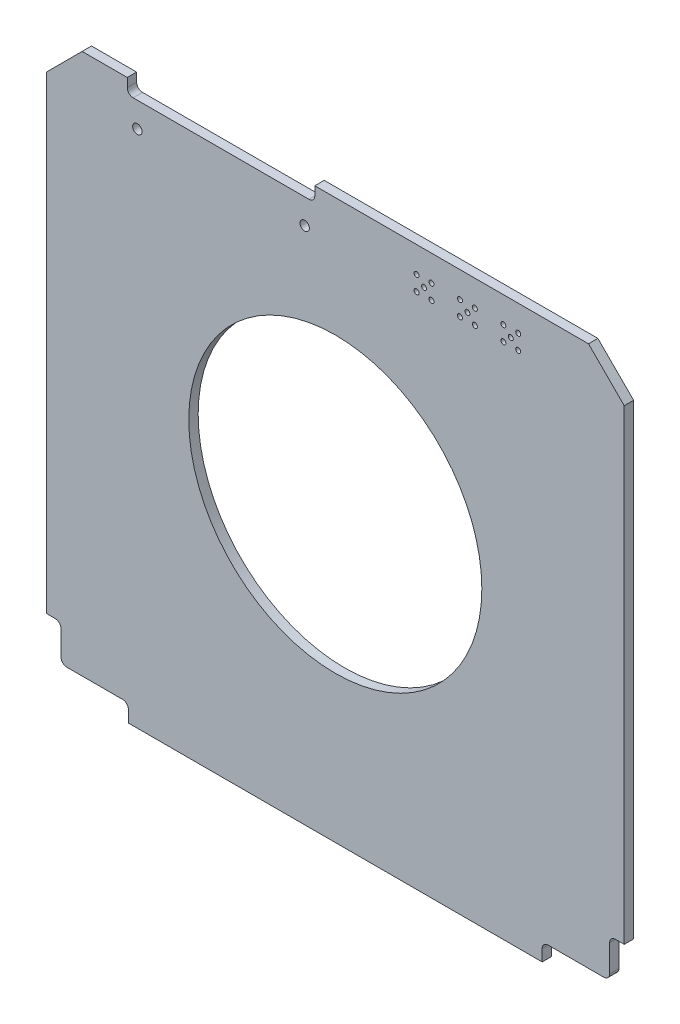
SolidWorks part; units mm, degrees
ref_plane "Front Plane" through (0, 0, 0) normal (0, 0, 1) x (1, 0, 0)
ref_plane "Top Plane" through (0, 0, 0) normal (0, 1, 0) x (1, 0, 0)
ref_plane "Right Plane" through (0, 0, 0) normal (1, 0, 0) x (0, 0, -1)
ref_plane "Plane1" through (0, 0, -0.0125) normal (0, 0, -1) x (-1, 0, 0)
sketch "Sketch1" plane through (0, 0, -0.0125) normal (0, 0, -1) x (-1, 0, 0)
  line L0 (47.8, -40.8) -> (49.3, -40.8)
  line L1 (49.3, -40.8) -> (49.3, 39.2)
  line L2 (49.3, 39.2) -> (43.2, 45.3)
  line L3 (43.2, 45.3) -> (35.5, 45.3)
  line L4 (35.5, 45.3) -> (35.5, 43.8)
  line L5 (34.5, 42.8) -> (4.5, 42.8)
  line L6 (3.5, 43.8) -> (3.5, 45.3)
  line L7 (3.5, 45.3) -> (-43.2, 45.3)
  line L8 (-43.2, 45.3) -> (-49.3, 39.2)
  line L9 (-49.3, 39.2) -> (-49.3, -40.4)
  line L10 (-49.3, -40.4) -> (-47.8, -40.4)
  line L11 (-46.8, -41.4) -> (-46.8, -46)
  line L12 (-45.8, -47) -> (-36.3, -47)
  line L13 (-35.3, -48) -> (-35.3, -50)
  line L14 (-35.3, -50) -> (35.3, -50)
  line L15 (35.3, -50) -> (35.3, -48)
  line L16 (36.3, -47) -> (45.8, -47)
  line L17 (46.8, -46) -> (46.8, -41.8)
  arc A0 (46.8, -41.8) -> (47.8, -40.8) centre (47.8, -41.8) cw
  arc A1 (35.5, 43.8) -> (34.5, 42.8) centre (34.5, 43.8) cw
  arc A2 (4.5, 42.8) -> (3.5, 43.8) centre (4.5, 43.8) cw
  arc A3 (-47.8, -40.4) -> (-46.8, -41.4) centre (-47.8, -41.4) cw
  arc A4 (-46.8, -46) -> (-45.8, -47) centre (-45.8, -46) ccw
  arc A5 (-36.3, -47) -> (-35.3, -48) centre (-36.3, -48) cw
  arc A6 (35.3, -48) -> (36.3, -47) centre (36.3, -48) cw
  arc A7 (45.8, -47) -> (46.8, -46) centre (45.8, -46) ccw
  circle A8 centre (-13.87, 38.33) radius 0.425
  circle A9 centre (0, 0) radius 25
  circle A10 centre (-22.54, 39.6) radius 0.425
  circle A11 centre (-23.81, 40.87) radius 0.425
  circle A12 centre (-21.27, 40.87) radius 0.425
  circle A13 centre (-13.87, 40.87) radius 0.425
  circle A14 centre (-31.21, 40.87) radius 0.425
  circle A15 centre (-16.41, 40.87) radius 0.425
  circle A16 centre (-15.14, 39.6) radius 0.425
  circle A17 centre (-29.94, 39.6) radius 0.425
  circle A18 centre (-28.67, 40.87) radius 0.425
  circle A19 centre (-28.67, 38.33) radius 0.425
  circle A20 centre (-16.41, 38.33) radius 0.425
  circle A21 centre (-21.27, 38.33) radius 0.425
  circle A22 centre (-23.81, 38.33) radius 0.425
  circle A23 centre (-31.21, 38.33) radius 0.425
  circle A24 centre (33.775, 38.54) radius 0.8
  circle A25 centre (5.225, 38.54) radius 0.8
extrude "Boss-Extrude1" add sketch "Sketch1" against normal blind 1.6
